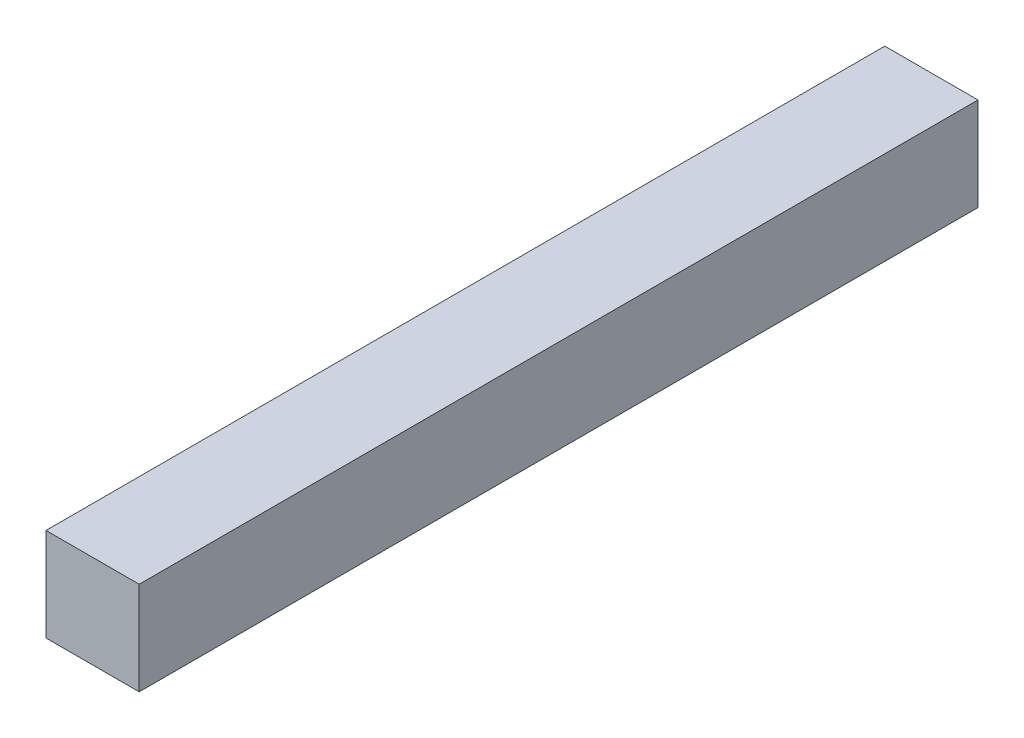
SolidWorks part; units mm, degrees
ref_plane "Alzado" through (0, 0, 0) normal (0, 0, 1) x (1, 0, 0)
ref_plane "Planta" through (0, 0, 0) normal (0, 1, 0) x (1, 0, 0)
ref_plane "Vista lateral" through (0, 0, 0) normal (1, 0, 0) x (0, 0, -1)
sketch "Croquis1" plane through (0, 0, 0) normal (1, 0, 0) x (0, 0, -1)
  line L1 (-225, 25) -> (225, 25)
  line L2 (-225, 25) -> (-225, -25)
  line L3 (-225, -25) -> (225, -25)
  line L4 (225, 25) -> (225, -25)
  line L5 (-225, 25) -> (225, -25) construction
  line L6 (-225, -25) -> (225, 25) construction
  point P0 (0, 0)
  dimension "D1" = 450
  dimension "D2" = 50
extrude "Saliente-Extruir1" add sketch "Croquis1" along normal blind 50
